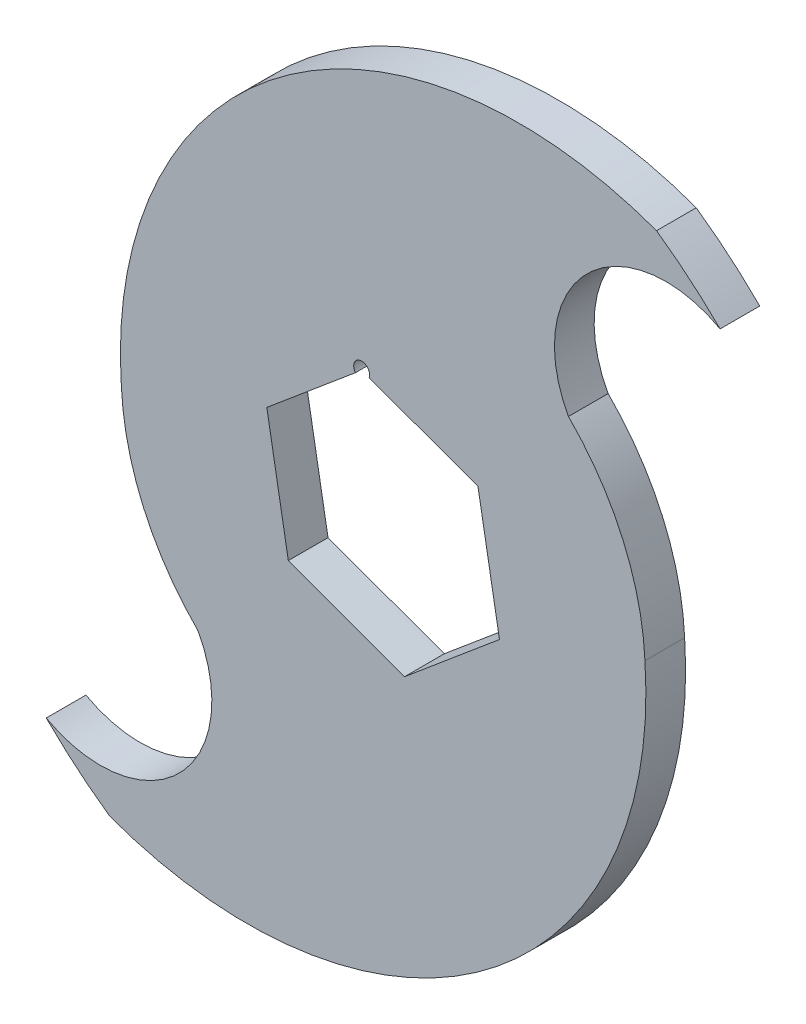
SolidWorks part; units mm, degrees
ref_plane "Front" through (0, 0, 0) normal (0, 0, 1) x (1, 0, 0)
ref_plane "Top" through (0, 0, 0) normal (0, 1, 0) x (1, 0, 0)
ref_plane "Right" through (0, 0, 0) normal (1, 0, 0) x (0, 0, -1)
sketch "Model" plane through (0, 0, 0) normal (0, 0, 1) x (1, 0, 0)
  line L0 (603.115, 76.0937) -> (589.4064, 81.0832)
  line L1 (587.7006, 80.7824) -> (576.5252, 71.4052)
  line L2 (576.5252, 71.4052) -> (579.2321, 56.0535)
  line L3 (579.2321, 56.0535) -> (593.8805, 50.722)
  line L4 (593.8805, 50.722) -> (605.822, 60.742)
  line L5 (605.822, 60.742) -> (603.115, 76.0937)
  arc A0 (625.6, 115.2144) -> (558.2085, 64.5572) centre (608.3, 68.0738) ccw
  arc A1 (558.2085, 64.5572) -> (567.8391, 42.7391) centre (591.1736, 66.0736) ccw
  arc A2 (548.7472, 23.6472) -> (567.8391, 42.7391) centre (555.5637, 35.9226) ccw
  arc A3 (548.7472, 23.6472) -> (556.7472, 16.9328) centre (591.1736, 66.0736) ccw
  arc A4 (556.7472, 16.9328) -> (624.1387, 67.59) centre (574.0472, 64.0734) ccw
  arc A5 (624.1387, 67.59) -> (614.5081, 89.4081) centre (591.1736, 66.0736) ccw
  arc A6 (633.6, 108.5) -> (614.5081, 89.4081) centre (626.7835, 96.2246) ccw
  arc A7 (633.6, 108.5) -> (625.6, 115.2144) centre (591.1736, 66.0736) ccw
  arc A8 (589.4064, 81.0832) -> (587.7006, 80.7824) centre (588.4667, 81.4252) ccw
extrude "Boss-Extrude1" add sketch "Model" along normal mid plane 5
